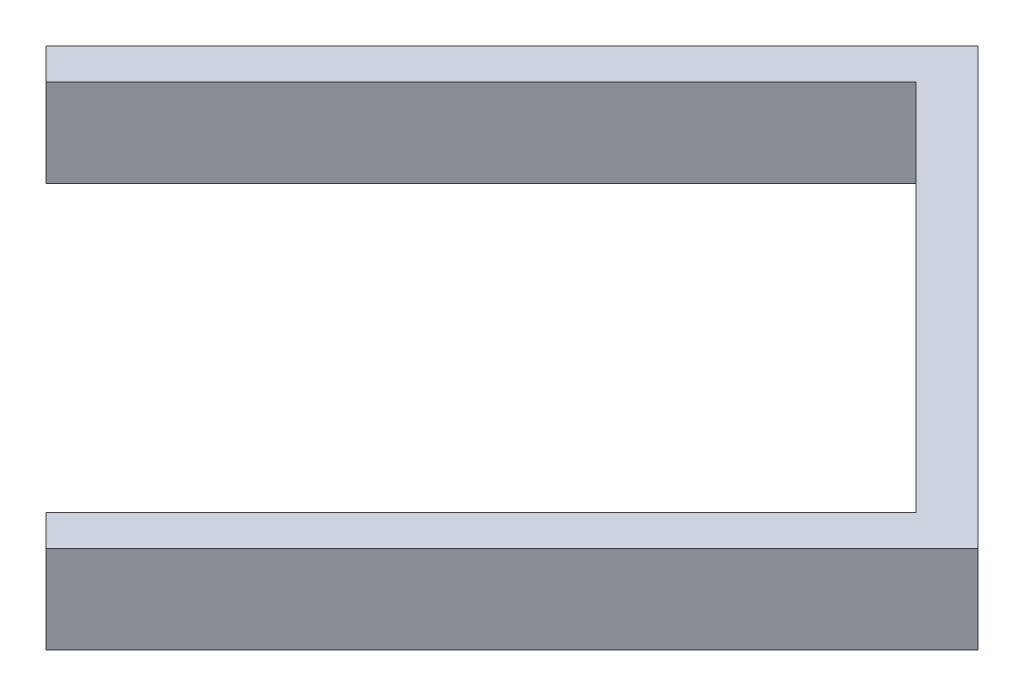
SolidWorks part; units mm, degrees
ref_plane "Front Plane" through (0, 0, 0) normal (0, 0, 1) x (1, 0, 0)
ref_plane "Top Plane" through (0, 0, 0) normal (0, 1, 0) x (1, 0, 0)
ref_plane "Right Plane" through (0, 0, 0) normal (1, 0, 0) x (0, 0, -1)
sketch "Sketch2" plane through (0, 0, 0) normal (0, 1, 0) x (1, 0, 0)
  line L0 (-240.1433, -24.0362) -> (-258.1038, -6.0757)
  line L1 (-258.1038, -6.0757) -> (11.3039, 263.332)
  line L2 (11.3039, 263.332) -> (262.7511, 11.8848)
  line L3 (262.7511, 11.8848) -> (-6.6566, -257.5229)
  line L4 (-6.6566, -257.5229) -> (-24.6171, -239.5624)
  line L5 (-24.6171, -239.5624) -> (226.83, 11.8848)
  line L6 (226.83, 11.8848) -> (11.3039, 227.4109)
  line L7 (11.3039, 227.4109) -> (-240.1433, -24.0362)
  line L8 (-118.8793, -118.2984) -> (119.067, 119.6479)
  point P10 (119.067, 119.6479)
  point P11 (0, 0)
  dimension "D1" = 25.4
  dimension "D2" = 25.4
  dimension "D3" = 304.8
  dimension "D4" = 355.6
extrude "Boss-Extrude2" add sketch "Sketch2" along normal blind 50.8 contours L7 L6 L5 L4 L3 L2 L1 L0
sketch "Sketch3" plane through (137.3179, 0, -137.3179) normal (0.7071, 0, -0.7071) x (-0.7071, 0, -0.7071)
  line L0 (178.2108, 50.8) -> (178.2108, 0) construction
  circle A0 centre (0, 25.4) radius 6.35
  point P2 (0, 23.3906)
  point P5 (178.2108, 25.4)
  dimension "D1" = 12.7
extrude "Cut-Extrude1" cut sketch "Sketch3" against normal blind 50.8
